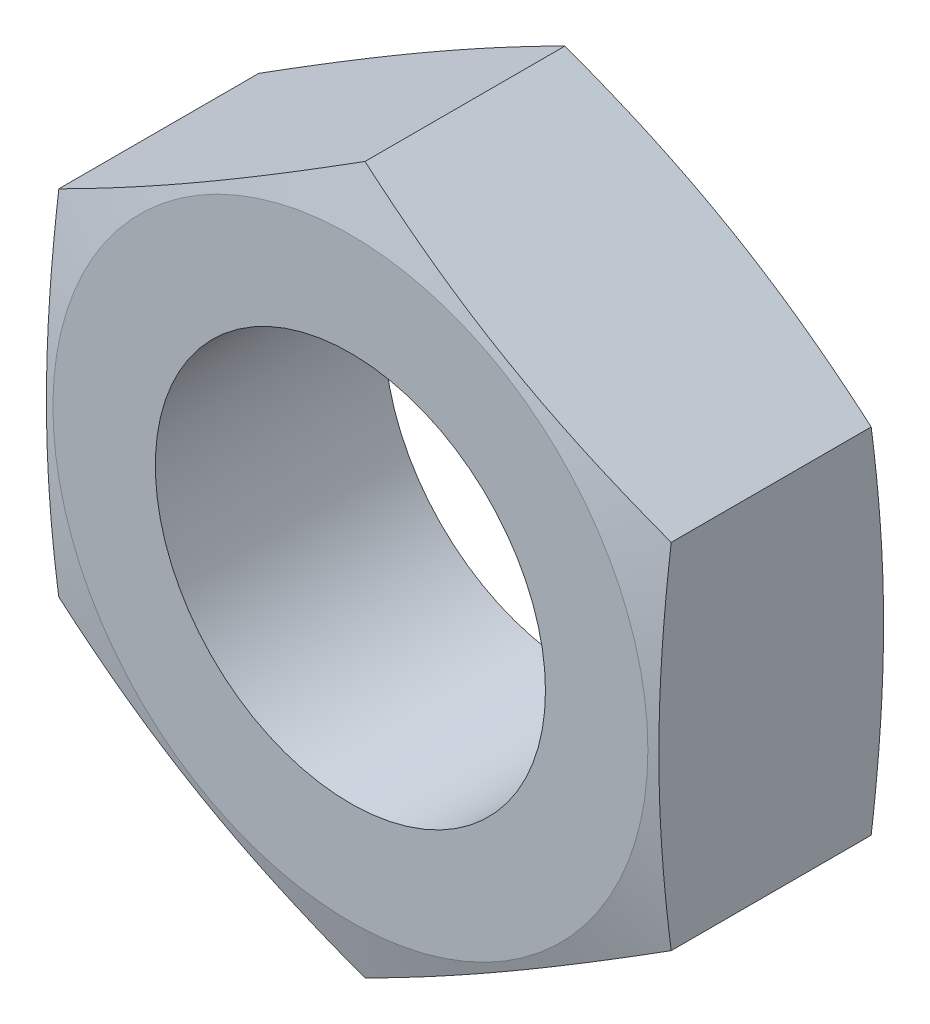
SolidWorks part; units mm, degrees
ref_plane "Спереди" through (0, 0, 0) normal (0, 0, 1) x (1, 0, 0)
ref_plane "Сверху" through (0, 0, 0) normal (0, 1, 0) x (1, 0, 0)
ref_plane "Справа" through (0, 0, 0) normal (1, 0, 0) x (0, 0, -1)
sketch "Эскиз2" plane through (0, 0, 0) normal (1, 0, 0) x (0, 0, -1)
  line L0 (0, 0) -> (47.3788, 0) construction
  line L1 (0, 4) -> (0, 6.1)
  line L2 (0, 6.1) -> (0.3, 7.25)
  line L3 (0.3, 7.25) -> (4.4, 7.25)
  line L4 (4.4, 7.25) -> (4.7, 6.1)
  line L5 (4.7, 6.1) -> (4.7, 4)
  line L6 (4.7, 4) -> (0, 4)
  dimension "D1" = 8
  dimension "D2" = 12.2
  dimension "D3" = 0.3
  dimension "D4" = 0.3
  dimension "D5" = 4.7
  dimension "D6" = 14.5
  dimension "D7" = 12.2
revolve "Повернуть1" add sketch "Эскиз2" angle 360 about L0
cosmetic thread "Условное изображение резьбы1" parameters "D2"=9
sketch "Эскиз3" plane through (0, 0, 0) normal (0, 0, 1) x (1, 0, 0)
  line L1 (0, 7.25) -> (-6.2787, 3.625)
  line L2 (-6.2787, 3.625) -> (-6.2787, -3.625)
  line L3 (-6.2787, -3.625) -> (0, -7.25)
  line L4 (0, -7.25) -> (6.2787, -3.625)
  line L5 (6.2787, -3.625) -> (6.2787, 3.625)
  line L6 (6.2787, 3.625) -> (0, 7.25)
  circle A0 centre (0, 0) radius 6.2787 construction
extrude "Вытянуть2" cut sketch "Эскиз3" against normal blind 4.7 flip side to cut
